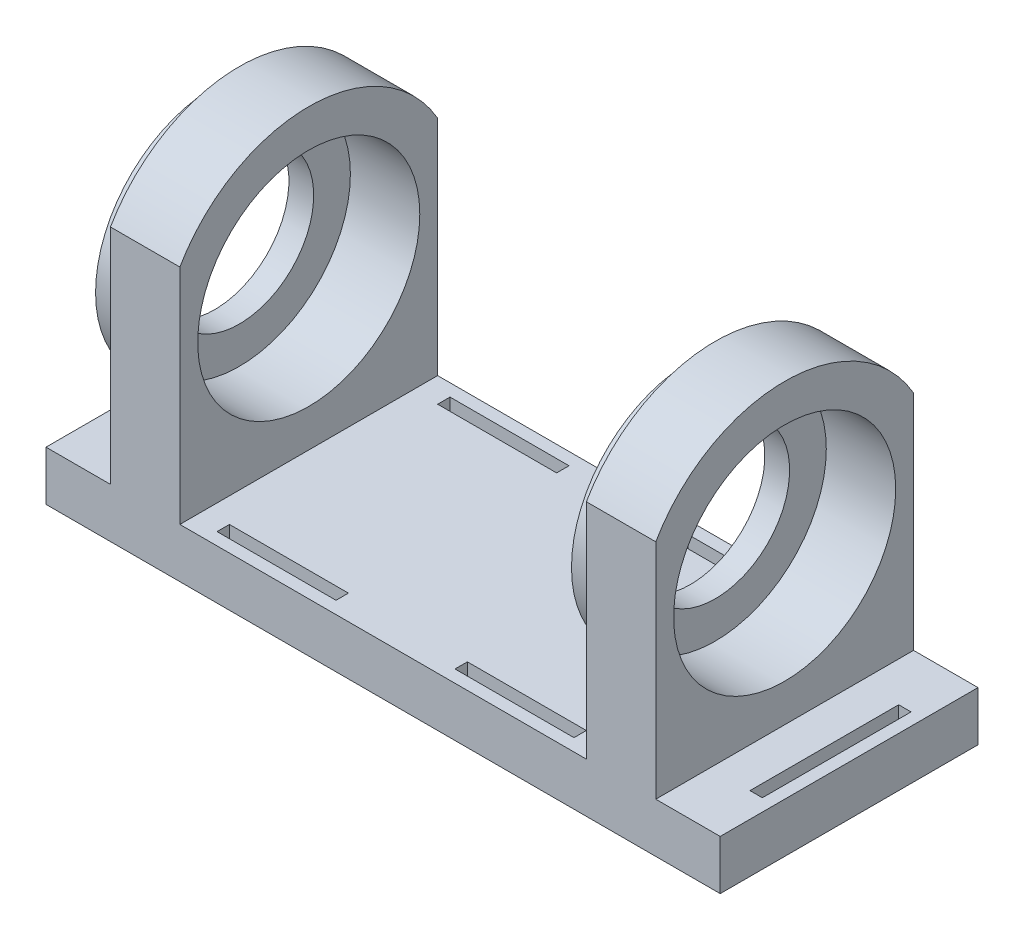
SolidWorks part; units mm, degrees
ref_plane "Front Plane" through (0, 0, 0) normal (0, 0, 1) x (1, 0, 0)
ref_plane "Top Plane" through (0, 0, 0) normal (0, 1, 0) x (1, 0, 0)
ref_plane "Right Plane" through (0, 0, 0) normal (1, 0, 0) x (0, 0, -1)
sketch "Sketch1" plane through (0, 0, 0) normal (0, 1, 0) x (1, 0, 0)
  line L0 (0, 0) -> (20, 0)
  line L1 (0, 0) -> (0, 26)
  line L2 (0, 26) -> (20, 26)
  line L3 (20, 26) -> (20, 0)
  line L4 (0, 26) -> (1.6662, 26)
  line L5 (2.5, 20.5) -> (2.5, 5.5)
  line L6 (20, 26) -> (16.6758, 26)
  line L8 (0, 26) -> (0.8331, 26)
  line L9 (1.25, 20.5) -> (1.25, 5.5)
  line L13 (0, 13) -> (20, 13) construction
  line L16 (2.5, 20.5) -> (1.25, 20.5)
  line L18 (2.5, 5.5) -> (1.25, 5.5)
  line L19 (10, 26) -> (10, 0) construction
  line L28 (14.1758, 26) -> (10, 26)
  dimension "D1" = 20
  dimension "D2" = 26
  dimension "D3" = 15
  dimension "D4" = 1.25
  dimension "D5" = 1.25
  dimension "D6" = 5.5
extrude "Boss-Extrude5" add sketch "Sketch1" along normal blind 5
sketch "Sketch3" plane through (0, 5, 0) normal (0, 1, 0) x (1, 0, 0)
  line L0 (2.5, 20.5) -> (2.5, 5.5) construction
  line L5 (6.5, 0) -> (13.5, 0)
  line L6 (6.5, 0) -> (6.5, 26)
  line L7 (6.5, 26) -> (13.5, 26)
  line L8 (13.5, 0) -> (13.5, 26)
  line L9 (6.5, 0) -> (13.5, 26) construction
  line L10 (6.5, 26) -> (13.5, 0) construction
  line L11 (0, 26) -> (20, 26) construction
  point P0 (10, 13)
  dimension "D1" = 7.5
  dimension "D2" = 7
  dimension "D3" = 26
  dimension "D4" = 13
extrude "Boss-Extrude6" add sketch "Sketch3" along normal blind 40
sketch "Sketch5" plane through (13.5, 0, 0) normal (1, 0, 0) x (0, 0, -1)
  line L2 (13, 45) -> (13, 5) construction
  line L3 (0, 45) -> (26, 45) construction
  line L4 (0, 5) -> (26, 5) construction
  line L5 (26, 5) -> (0, 5) construction
  line L6 (0, 27.4833) -> (0, 45)
  line L7 (0, 45) -> (26, 45)
  line L10 (26, 45) -> (26, 27.4833)
  line L16 (26, 45) -> (26, 5) construction
  circle A0 centre (13, 20) radius 11.2
  arc A3 (26, 27.4833) -> (0, 27.4833) centre (13, 20) ccw
  dimension "D1" = 15
  dimension "D2" = 22.4
  dimension "D3" = 30
extrude "Cut-Extrude1" cut sketch "Sketch5" against normal up to next
sketch "Sketch6" plane through (20, 0, 0) normal (1, 0, 0) x (0, 0, -1)
  line L1 (0, 0) -> (26, 0)
  line L2 (0, 0) -> (0, 5)
  line L3 (0, 5) -> (26, 5)
  line L4 (26, 0) -> (26, 5)
extrude "Boss-Extrude8" add sketch "Sketch6" along normal blind 14
mirror "Mirror5" about plane through (34, 0, 0) normal (-1, 0, 0) of "Cut-Extrude1", "Boss-Extrude8", "Boss-Extrude6", "Boss-Extrude5"
sketch "Sketch7" plane through (0, 5, 0) normal (0, 1, 0) x (1, 0, 0)
  line L0 (34, 26) -> (34, 0) construction
  line L5 (13.5, 0) -> (13.5, 26) construction
  line L6 (16, 2.5) -> (28, 2.5)
  line L7 (16, 2.5) -> (16, 1.25)
  line L8 (13.5, 0) -> (54.5, 0) construction
  line L9 (13.5, 0) -> (13.5, 26) construction
  line L10 (13.5, 13) -> (54.5, 13) construction
  line L11 (16, 1.25) -> (28, 1.25)
  line L12 (28, 2.5) -> (28, 1.25)
  line L13 (54.5, 0) -> (54.5, 26) construction
  line L14 (13.5, 26) -> (54.5, 26) construction
  line L15 (40, 2.5) -> (40, 1.25)
  line L16 (52, 1.25) -> (40, 1.25)
  line L17 (52, 2.5) -> (52, 1.25)
  line L18 (52, 2.5) -> (40, 2.5)
  line L19 (52, 23.5) -> (40, 23.5)
  line L20 (52, 23.5) -> (52, 24.75)
  line L21 (52, 24.75) -> (40, 24.75)
  line L22 (40, 23.5) -> (40, 24.75)
  line L23 (28, 23.5) -> (28, 24.75)
  line L24 (16, 24.75) -> (28, 24.75)
  line L25 (16, 23.5) -> (16, 24.75)
  line L26 (16, 23.5) -> (28, 23.5)
  dimension "D1" = 1.25
  dimension "D2" = 12
  dimension "D3" = 1.25
  dimension "D4" = 2.5
sketch "Sketch8" plane through (6.5, 0, 0) normal (-1, 0, 0) x (0, 0, 1)
  circle A0 centre (-13, 20) radius 11.2 construction
  circle A3 centre (-13, 20) radius 12
  circle A4 centre (-13, 20) radius 7.5
  point P4 (-13, 20)
  dimension "D1" = 15
  dimension "D2" = 24
extrude "Boss-Extrude9" add sketch "Sketch8" along normal blind 2.5
sketch "Sketch9" plane through (54.5, 0, 0) normal (-1, 0, 0) x (0, 0, 1)
  circle A0 centre (-13, 20) radius 7.5 construction
  circle A1 centre (-13, 20) radius 12
  circle A2 centre (-13, 20) radius 12
  circle A3 centre (-13, 20) radius 7.5
  dimension "D1" = 0
extrude "Boss-Extrude10" add sketch "Sketch9" along normal blind 2.5
extrude "Cut-Extrude2" cut sketch "Sketch7" against normal blind 10
